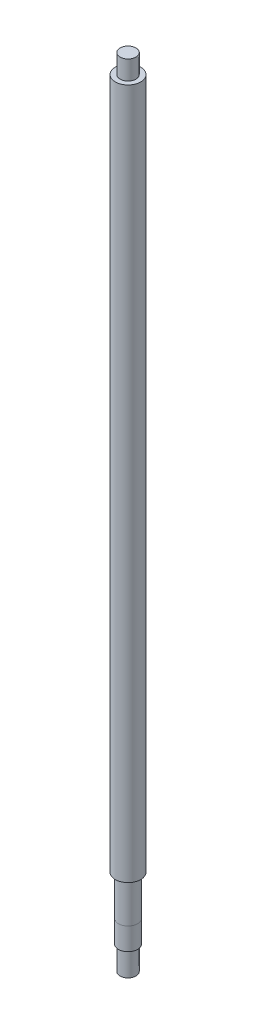
SolidWorks part; units mm, degrees
ref_plane "Front Plane" through (0, 0, 0) normal (0, 0, 1) x (1, 0, 0)
ref_plane "Top Plane" through (0, 0, 0) normal (0, 1, 0) x (1, 0, 0)
ref_plane "Right Plane" through (0, 0, 0) normal (1, 0, 0) x (0, 0, -1)
ref_plane "Plane1"
sketch "Sketch1" plane through (0, 0, 0) normal (0, 1, 0) x (-1, 0, 0)
  circle A0 centre (0, 0) radius 8
  dimension "D1" = 16
extrude "Extrusion1" add sketch "Sketch1" along normal blind 500
sketch "Sketch2" plane through (0, 0, 0) normal (0, -1, 0) x (1, 0, 0)
  circle A0 centre (0, 0) radius 8
extrude "Extrusion2" cut sketch "Sketch2" against normal blind 50
sketch "Sketch3" plane through (0, 50, 0) normal (0, -1, 0) x (1, 0, 0)
  circle A0 centre (0, 0) radius 8
extrude "Extrusion3" add sketch "Sketch3" along normal blind 50
sketch "Sketch4" plane through (0, 0, 0) normal (0, -1, 0) x (1, 0, 0)
  circle A0 centre (0, 0) radius 8
  circle A1 centre (0, 0) radius 6
extrude "Thread1" cut sketch "Sketch4" against normal blind 14
cosmetic thread "Cosmetic Thread1" parameters "D2"=0
ref_plane "Plane2"
sketch "Sketch5" plane through (0, 14, 0) normal (0, -1, 0) x (1, 0, 0)
  circle A0 centre (0, 0) radius 8
  circle A1 centre (0, 0) radius 6.05
  dimension "D1" = 12.1
extrude "Extrusion5" cut sketch "Sketch5" against normal blind 25 contours A0 A1
sketch "Sketch6" plane through (0, 0, 0) normal (0, -1, 0) x (1, 0, 0)
  circle A0 centre (0, 0) radius 5
  dimension "D1" = 10
extrude "Extrusion6" add sketch "Sketch6" along normal blind 15
sketch "Sketch7" plane through (0, 500, 0) normal (0, 1, 0) x (-1, 0, 0)
  circle A0 centre (0, 0) radius 8
extrude "Extrusion7" cut sketch "Sketch7" against normal blind 27.101
sketch "Sketch8" plane through (0, 472.899, 0) normal (0, 1, 0) x (-1, 0, 0)
  circle A0 centre (0, 0) radius 5
  dimension "D1" = 10
extrude "Extrusion8" add sketch "Sketch8" along normal blind 12
